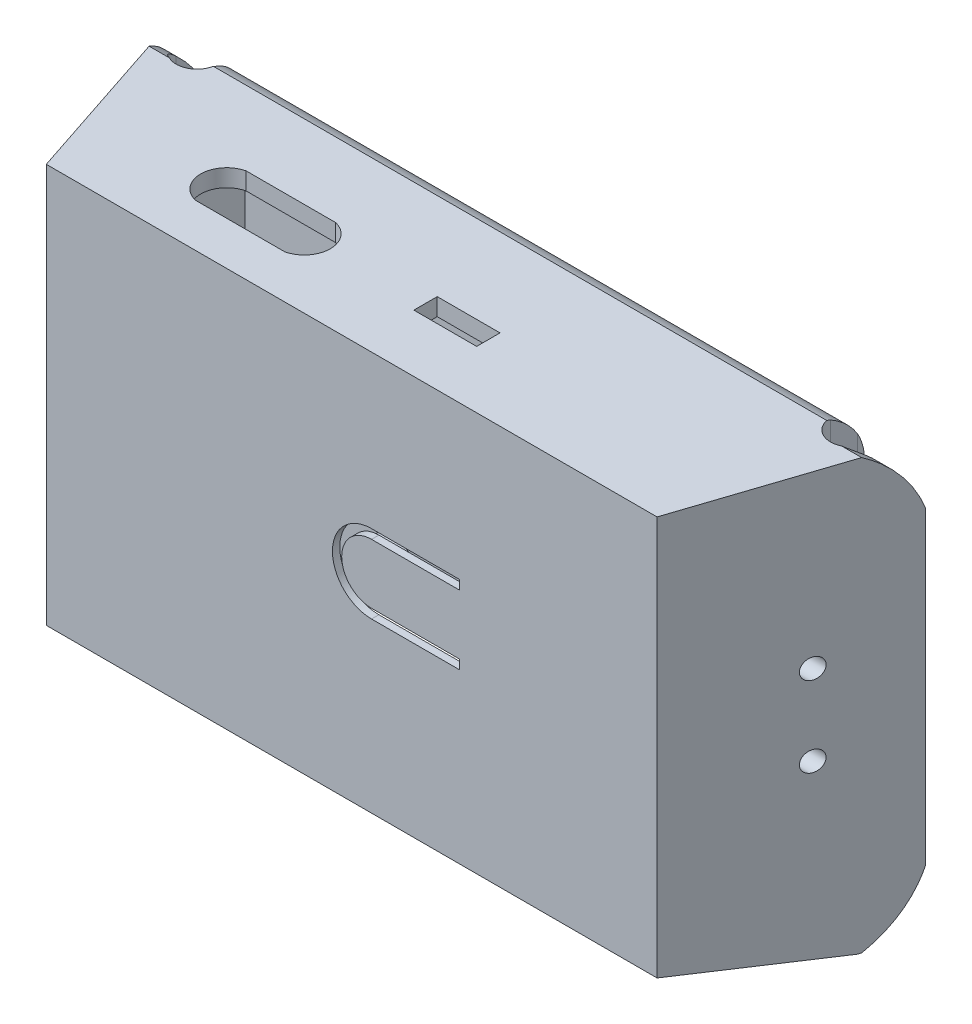
SolidWorks part; units mm, degrees
ref_plane "Plan de face" through (0, 0, 0) normal (0, 0, 1) x (1, 0, 0)
ref_plane "Plan de dessus" through (0, 0, 0) normal (0, 1, 0) x (1, 0, 0)
ref_plane "Plan de droite" through (0, 0, 0) normal (1, 0, 0) x (0, 0, -1)
sketch "Esquisse1" plane through (0, 0, 0) normal (0, 0, 1) x (1, 0, 0)
  line L1 (-22.85, -14.35) -> (22.85, -14.35)
  line L2 (-22.85, -14.35) -> (-22.85, 14.35)
  line L3 (-22.85, 14.35) -> (22.85, 14.35)
  line L4 (22.85, -14.35) -> (22.85, 14.35)
  line L5 (-22.85, -14.35) -> (22.85, 14.35) construction
  line L6 (-22.85, 14.35) -> (22.85, -14.35) construction
  point P0 (0, 0)
  dimension "D1" = 45.7
  dimension "D2" = 28.7
extrude "Boss.-Extru.1" add sketch "Esquisse1" along normal blind 15.1
sketch "Esquisse2" plane through (0, -14.35, 0) normal (0, -1, 0) x (1, 0, 0)
  line L0 (-22.85, 0) -> (22.85, 0) construction
  line L2 (-22.05, 1.05) -> (22.05, 1.05)
  line L3 (-22.05, 1.05) -> (-22.05, 14.55)
  line L4 (-22.05, 14.55) -> (22.05, 14.55)
  line L5 (22.05, 1.05) -> (22.05, 14.55)
  line L6 (-22.05, 1.05) -> (22.05, 14.55) construction
  line L7 (-22.05, 14.55) -> (22.05, 1.05) construction
  dimension "D1" = 44.1
  dimension "D2" = 13.5
  dimension "D3" = 1.05
extrude "Enlèv. mat.-Extru.1" cut sketch "Esquisse2" against normal blind 27.9 contours L3 L2 L5 L4
sketch "Esquisse3" plane through (0, 0, 1.05) normal (0, 0, 1) x (1, 0, 0)
  line L0 (-22.05, -14.35) -> (22.05, -14.35) construction
  line L1 (22.05, 13.55) -> (19.0098, 13.55)
  line L2 (22.05, 13.55) -> (22.05, -14.35)
  line L3 (22.05, -14.35) -> (19.0098, -14.35)
  line L4 (19.0098, 13.55) -> (19.0098, -14.35)
extrude "Boss.-Extru.2" add sketch "Esquisse3" along normal blind 1.3
sketch "Esquisse4" plane through (0, 0, 15.1) normal (0, 0, 1) x (1, 0, 0)
  line L1 (1.4872, 2.2155) -> (8.0777, 2.2155)
  line L3 (8.0777, -2.2527) -> (1.4872, -2.2527)
  line L5 (1.4872, -2.9455) -> (8.0777, -2.9455)
  line L6 (1.4872, 2.9083) -> (8.0777, 2.9083)
  line L7 (8.0777, 2.9083) -> (8.0777, 2.2155)
  line L8 (8.0777, -2.9455) -> (8.0777, -2.2527)
  arc A0 (1.4872, 2.9083) -> (1.4872, -2.9455) centre (1.4872, -0.0186) ccw
  arc A1 (1.4872, 2.2155) -> (1.4872, -2.2527) centre (1.4872, -0.0186) ccw
extrude "Enlèv. mat.-Extru.2" cut sketch "Esquisse4" against normal blind 1.3
sketch "Esquisse5" plane through (0, 0, 14.55) normal (0, 0, -1) x (-1, 0, 0)
  circle A0 centre (-1.4872, -0.0186) radius 1.7367
extrude "Boss.-Extru.3" add sketch "Esquisse5" along normal blind 1
sketch "Esquisse6" plane through (0, 13.55, 0) normal (0, -1, 0) x (1, 0, 0)
  line L0 (5.05, -3.4715) -> (5.05, 21.2369)
  line L1 (-22.05, 1.05) -> (-22.05, 14.55) construction
  line L2 (0.35, -5.9282) -> (0.35, 19.3944)
  line L3 (22.05, 2.35) -> (22.05, 14.55) construction
  line L4 (-29.0784, 10.25) -> (26.2438, 10.25)
  line L6 (-22.05, 1.05) -> (19.0098, 1.05) construction
  line L7 (-27.9446, 9.05) -> (24.5431, 9.05)
  line L8 (0.35, 10.8) -> (5.05, 10.8)
  line L9 (0.35, 10.8) -> (0.35, 9.05)
  line L10 (0.35, 9.05) -> (5.05, 9.05)
  line L11 (5.05, 10.8) -> (5.05, 9.05)
  dimension "D1" = 27.1
  dimension "D2" = 21.7
  dimension "D3" = 55.3223
  dimension "D4" = 9.2
  dimension "D5" = 8
  dimension "D6" = 9.75
extrude "Enlèv. mat.-Extru.3" cut sketch "Esquisse6" against normal blind 10.5 contours L9 L8 L11 L10
sketch "Esquisse7" plane through (0, 13.55, 0) normal (0, -1, 0) x (1, 0, 0)
  line L0 (-6.75, -4.0857) -> (-6.75, 20.6227)
  line L1 (-22.05, 1.05) -> (-22.05, 14.55) construction
  line L2 (-16.45, -2.9046) -> (-16.45, 22.9849)
  line L3 (22.05, 2.35) -> (22.05, 14.55) construction
  line L4 (-28.0863, 11.85) -> (30.2123, 11.85)
  line L5 (-22.05, 1.05) -> (19.0098, 1.05) construction
  line L6 (-19.0156, 8.05) -> (-1.9606, 8.05)
  line L7 (-14.95, 12.1224) -> (-14.95, 6.7367)
  line L8 (-8.25, 11.9991) -> (-8.25, 6.7367)
  line L9 (-14.95, 11.85) -> (-8.25, 11.85)
  line L10 (-8.25, 8.05) -> (-14.95, 8.05)
  arc A0 (-14.95, 11.85) -> (-14.95, 8.05) centre (-14.4967, 9.95) ccw
  arc A1 (-8.25, 11.85) -> (-8.25, 8.05) centre (-8.7033, 9.95) cw
  dimension "D1" = 15.3
  dimension "D2" = 38.5
  dimension "D3" = 10.8
  dimension "D4" = 3.8
  dimension "D5" = 1.5
  dimension "D6" = 1.5
extrude "Enlèv. mat.-Extru.4" cut sketch "Esquisse7" against normal blind 10.5 contours L10 A0 L9 A1
sketch "Esquisse9" plane through (0, 14.35, 0) normal (0, 1, 0) x (1, 0, 0)
  line L7 (22.85, -15.1) -> (-22.85, -15.1) construction
  line L9 (22.85, 0) -> (22.85, -15.1)
  line L12 (-22.85, 0) -> (-22.85, -15.1)
  line L13 (-22.85, -15.1) -> (-27.85, 0)
  line L14 (-27.85, 0) -> (-22.85, 0)
  line L15 (22.85, -15.1) -> (27.85, 0)
  line L16 (27.85, 0) -> (22.85, 0)
extrude "Boss.-Extru.5" add sketch "Esquisse9" against normal blind 28.7 contours L14 L12 L13 | L16 L9 L15
sketch "Esquisse11" plane through (0, 14.35, 0) normal (0, 1, 0) x (1, 0, 0)
  line L0 (-31.641, -4.4) -> (28.9922, -4.4)
  line L1 (27.85, 0) -> (-27.85, 0) construction
  line L2 (-22.85, -15.1) -> (-22.85, 3.986)
  line L3 (22.85, -15.1) -> (22.85, -4.4)
  line L4 (26.1, -10.388) -> (26.1, 3.219)
  line L5 (-26.1, -7.1473) -> (-26.1, 3.986)
  line L14 (-37.3297, -2.2) -> (30.1079, -2.2)
  line L15 (-25.7062, 0) -> (-23.2375, 0)
  line L16 (23.2539, 0) -> (25.7066, 0)
  line L17 (-25.7062, 0) -> (-25.7062, -0.5176)
  line L18 (-25.7062, -0.5176) -> (-26.0292, -2.2)
  line L19 (-22.9208, -2.2) -> (-23.2375, -0.5176)
  line L20 (-23.2375, -0.5176) -> (-23.2375, 0)
  line L21 (22.9208, -2.2) -> (23.2539, -0.5176)
  line L22 (23.2539, -0.5176) -> (23.2539, 0)
  line L23 (26.0301, -2.2) -> (25.7066, -0.4643)
  line L24 (25.7066, -0.4643) -> (25.7066, 0)
  arc A0 (-26.0292, -2.2) -> (-22.9208, -2.2) centre (-24.475, -2.2) ccw
  arc A1 (22.9208, -2.2) -> (26.0301, -2.2) centre (24.4755, -2.2) ccw
  dimension "D1" = 4.4
  dimension "D2" = 3.25
  dimension "D3" = 3.25
  dimension "D8" = 2.2
extrude "Enlèv. mat.-Extru.6" cut sketch "Esquisse11" against normal blind 28.7 contours L15 L20 L19 A0 L18 L17 | L16 L24 L23 A1 L21 L22
sketch "Esquisse17" plane through (0, -14.35, 0) normal (0, -1, 0) x (-1, 0, 0)
  line L8 (27.85, 0) -> (22.85, -15.1)
  line L9 (22.85, -15.1) -> (22.05, -15.1)
  line L10 (22.85, -15.1) -> (-22.85, -15.1) construction
  line L11 (22.05, -15.1) -> (22.05, -1.05)
  line L13 (-27.85, 0) -> (-22.85, -15.1)
  line L21 (-22.0559, -15.1) -> (-22.85, -15.1)
  line L24 (22.05, -1.05) -> (22.05, 0)
  line L25 (23.2375, -0.5176) -> (23.2375, 0)
  line L26 (23.2375, -0.5176) -> (23.2375, 0) construction
  line L27 (23.2375, 0) -> (-23.2539, 0) construction
  line L28 (25.7062, 0) -> (27.85, 0)
  line L29 (25.7062, 0) -> (25.7062, -0.5176)
  line L30 (25.7062, -0.5176) -> (26.0292, -2.2)
  line L31 (22.05, 0) -> (23.2375, 0)
  line L32 (23.2375, -0.5176) -> (22.9208, -2.2)
  line L33 (-27.85, 0) -> (-25.7066, 0)
  line L34 (-25.7066, 0) -> (-25.7066, -0.4643)
  line L35 (-25.7066, -0.4643) -> (-26.0301, -2.2)
  line L36 (-22.9208, -2.2) -> (-23.2539, -0.5176)
  line L37 (-22.9208, -2.2) -> (-23.2539, -0.5176) construction
  line L38 (-23.2539, -0.5176) -> (-23.2539, 0)
  line L39 (-22.0559, -15.1) -> (-22.0559, 0)
  line L40 (-22.0559, 0) -> (-23.2539, 0)
  arc A1 (22.9208, -2.2) -> (26.0292, -2.2) centre (24.475, -2.2) ccw construction
  arc A3 (22.9208, -2.2) -> (26.0292, -2.2) centre (24.475, -2.2) ccw construction
  arc A4 (22.9208, -2.2) -> (26.0292, -2.2) centre (24.475, -2.2) ccw
  arc A5 (-26.0301, -2.2) -> (-22.9208, -2.2) centre (-24.4755, -2.2) ccw construction
  arc A6 (-26.0301, -2.2) -> (-22.9208, -2.2) centre (-24.4755, -2.2) ccw
extrude "Boss.-Extru.7" add sketch "Esquisse17" along normal blind 3.4
sketch "Esquisse25" plane through (0, 0, 0) normal (0, 0, -1) x (-1, 0, 0)
  line L1 (-22.778, -14.3591) -> (22.6834, -14.3591)
  line L3 (-22.778, -15.2591) -> (22.6834, -15.2591)
  line L7 (-22.778, -15.2591) -> (-22.778, -14.3591)
  line L8 (-22.778, -14.3591) -> (22.6834, -14.3591)
  line L9 (22.6834, -14.3591) -> (22.6834, -15.2591)
  line L10 (22.6834, -15.2591) -> (-22.778, -15.2591)
extrude "Enlèv. mat.-Extru.14" cut sketch "Esquisse25" against normal blind 14 contours L10 L7 L8 L9
sketch "Esquisse26" plane through (-22.05, 0, 0) normal (1, 0, 0) x (0, 0, -1)
  line L2 (-3.85, -17.75) -> (-15.1, -15.5274)
  line L3 (-15.1, -17.75) -> (-15.1, -14.35) construction
  line L4 (-15.1, -15.5274) -> (-15.1, -17.75)
  line L5 (-15.1, -17.75) -> (-3.85, -17.75)
  line L6 (0, -17.75) -> (-15.1, -17.75) construction
extrude "Enlèv. mat.-Extru.15" cut sketch "Esquisse26" against normal mid plane 114 contours L5 L2 L4
sketch "Esquisse31" plane through (22.0559, 0, 0) normal (-1, 0, 0) x (0, 0, 1)
  line L1 (14.0027, -14.35) -> (14.0027, -15.7442)
  line L7 (15.1, -14.35) -> (14.0027, -14.35)
  line L8 (15.1, -14.35) -> (15.1, -15.5274)
  line L10 (14.0027, -15.7442) -> (15.1, -15.5274)
  line L11 (3.85, -17.75) -> (15.1, -15.5274) construction
extrude "Boss.-Extru.9" add sketch "Esquisse31" along normal blind 44.3
sketch "Esquisse32" plane through (22.05, 0, 0) normal (-1, 0, 0) x (0, 0, 1)
  line L0 (6.35, 13.55) -> (6.35, -14.35)
  line L1 (2.35, 13.55) -> (14.55, 13.55) construction
  line L2 (2.35, -14.35) -> (2.35, 13.55) construction
  line L3 (2.35, -0.4) -> (8.9459, -0.4)
  line L4 (2.35, -14.35) -> (14.0027, -14.35) construction
  line L5 (3.8182, 1.6) -> (8.8818, 1.6)
  line L6 (4.0648, -4.4) -> (8.6352, -4.4)
  circle A0 centre (6.35, 1.6) radius 0.75
  circle A1 centre (6.35, -4.4) radius 0.75
  dimension "D6" = 1.5
  dimension "D7" = 1.5
  dimension "D1" = 4
  dimension "D2" = 13.95
  dimension "D3" = 13.95
  dimension "D4" = 4
  dimension "D5" = 2
extrude "Enlèv. mat.-Extru.17" cut sketch "Esquisse32" against normal blind 44.3 contours A0 | A1
sketch "Esquisse35" plane through (0, 13.55, 0) normal (0, -1, 0) x (1, 0, 0)
  line L0 (-22.05, 14.0027) -> (-22.05, 1.05)
  line L1 (-22.05, 1.05) -> (19.0098, 1.05)
  line L2 (19.0098, 1.05) -> (19.0098, 2.35)
  line L3 (19.0098, 2.35) -> (22.05, 2.35)
  line L4 (22.05, 2.35) -> (22.0559, 14.0027)
  line L5 (22.0559, 14.0027) -> (-22.05, 14.0027)
  line L6 (0.35, 10.8) -> (5.05, 10.8)
  line L7 (5.05, 10.8) -> (5.05, 9.05)
  line L8 (5.05, 9.05) -> (0.35, 9.05)
  line L9 (0.35, 9.05) -> (0.35, 10.8)
  line L10 (-14.95, 11.85) -> (-8.25, 11.85)
  line L11 (-14.95, 11.85) -> (-8.25, 11.85) construction
  line L12 (-14.95, 8.05) -> (-8.25, 8.05)
  arc A0 (-8.25, 8.05) -> (-8.25, 11.85) centre (-8.7033, 9.95) ccw construction
  arc A1 (-8.25, 11.85) -> (-8.25, 8.05) centre (-8.7033, 9.95) cw
  arc A2 (-14.95, 11.85) -> (-14.95, 8.05) centre (-14.4967, 9.95) ccw
extrude "Boss.-Extru.10" add sketch "Esquisse35" along normal blind 0.5
sketch "Esquisse34" plane through (-22.05, 0, 0) normal (1, 0, 0) x (0, 0, -1)
  line L0 (-2.5, -16.9369) -> (-2.5, 22.3048)
  line L1 (0, -17.75) -> (0, 14.35) construction
  line L2 (-2.5, -16.9369) -> (-2.5, -23.0408)
  line L3 (6.3183, 11.05) -> (-23.4343, 11.05)
  line L4 (3.3645, -14.45) -> (-18.9457, -14.45)
  line L5 (-3.85, -17.75) -> (0, -17.75) construction
  line L6 (-15.1, 14.35) -> (0, 14.35) construction
  line L7 (0, -17.75) -> (0, 14.35) construction
  line L8 (0, 11.05) -> (2.1498, 13.4667)
  line L9 (2.1498, 13.4667) -> (2.705, 17.1998)
  line L10 (2.705, 17.1998) -> (-2.5, 14.35)
  line L11 (0, -14.45) -> (2.6155, -12.4384)
  line L12 (2.6155, -12.4384) -> (4.6472, -16.8989)
  line L13 (4.6472, -16.8989) -> (-1.3121, -20.336)
  line L14 (-1.3121, -20.336) -> (-2.5, -17.75)
  arc A0 (-2.5, 14.35) -> (0, 11.05) centre (-3.9039, 10.6895) cw
  arc A1 (-2.5, -17.75) -> (0, -14.45) centre (-3.9039, -14.0895) ccw
  dimension "D1" = 2.5
  dimension "D2" = 3.3
  dimension "D3" = 3.3
extrude "Enlèv. mat.-Extru.19" cut sketch "Esquisse34" along normal blind 74.3 from offset 10 contours L10 A0 L8 L9 | L14 A1 L11 L12 L13 offset against normal yes
sketch "Esquisse36" plane through (-22.05, 0, 0) normal (1, 0, 0) x (0, 0, -1)
  line L0 (-3.6, -20.5968) -> (-3.6, 16.1397)
  line L1 (-21.5991, 9.85) -> (3.8733, 9.85)
  line L2 (-23.235, -13.25) -> (9.7157, -13.25)
  line L3 (-3.175, -17.75) -> (-25.7589, -17.75)
  line L4 (0, -14.45) -> (0, 11.05) construction
  line L5 (-15.1, 14.35) -> (-2.5, 14.35) construction
  line L6 (-2.5, -17.75) -> (-3.85, -17.75) construction
  line L7 (-3.6, 14.35) -> (0.2331, 16.1397)
  line L8 (0.2331, 16.1397) -> (1.2816, 9.285)
  line L9 (1.2816, 9.285) -> (0, 9.85)
  line L10 (0, -13.25) -> (2.4086, -12.1254)
  line L11 (2.4086, -12.1254) -> (1.2043, -19.6341)
  line L12 (1.2043, -19.6341) -> (-3.6, -17.75)
  arc A0 (-3.6, -17.75) -> (0, -13.25) centre (-7.4156, -11.0075) ccw
  arc A1 (0, 9.85) -> (-3.6, 14.35) centre (-7.6893, 7.3886) ccw
  dimension "D1" = 4.5
  dimension "D2" = 4.5
  dimension "D3" = 3.6
extrude "Enlèv. mat.-Extru.20" cut sketch "Esquisse36" against normal blind 5 from offset 2.2 contours L9 A1 L7 L8 | L12 A0 L10 L11 offset against normal yes
sketch "Esquisse37" plane through (22.05, 0, 0) normal (-1, 0, 0) x (0, 0, 1)
  line L0 (3.6, -13.4256) -> (3.6, 15.7276)
  line L1 (0, -14.45) -> (0, 11.05) construction
  line L2 (2.8785, -17.75) -> (22.9725, -17.75)
  line L3 (2.5, -17.75) -> (3.85, -17.75) construction
  line L4 (3.6, -19.4263) -> (3.6, -17.75)
  line L5 (20.1994, 9.85) -> (-10.3896, 9.85)
  line L6 (15.1, 14.35) -> (2.5, 14.35) construction
  line L7 (3.6, 14.35) -> (1.252, 16.698)
  line L8 (1.252, 16.698) -> (-2.7726, 8.3537)
  line L9 (-2.7726, 8.3537) -> (0, 9.85)
  line L10 (0, -13.25) -> (-1.9549, -12.3071)
  line L11 (-1.9549, -12.3071) -> (-2.275, -21.3106)
  line L12 (-2.275, -21.3106) -> (3.6, -19.4263)
  arc A0 (3.6, 14.35) -> (0, 9.85) centre (7.739, 7.3488) ccw
  arc A1 (0, -13.25) -> (3.6, -17.75) centre (7.7044, -10.7765) ccw
  dimension "D1" = 3.6
  dimension "D2" = 4.5
extrude "Enlèv. mat.-Extru.21" cut sketch "Esquisse37" against normal blind 5 from offset 2.2 contours L9 A0 L7 L8 | L4 A1 L10 L11 L12 offset against normal yes
sketch "Esquisse40" plane through (22.0559, 0, 0) normal (-1, 0, 0) x (0, 0, 1)
  line L2 (3.85, -17.75) -> (14.0027, -15.7442) construction
  line L4 (14, -15.2591) -> (14, -15.7447)
